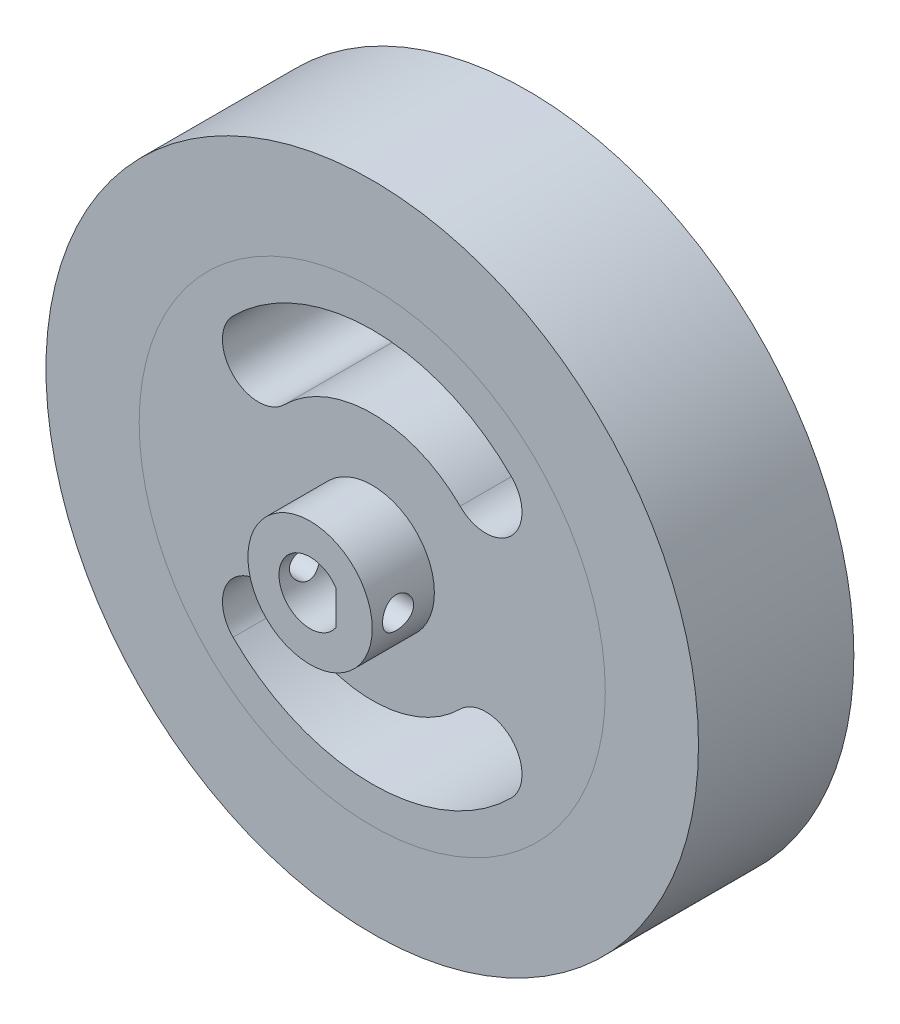
SolidWorks part; units mm, degrees
ref_plane "前视基准面" through (0, 0, 0) normal (0, 0, 1) x (1, 0, 0)
ref_plane "上视基准面" through (0, 0, 0) normal (0, 1, 0) x (1, 0, 0)
ref_plane "右视基准面" through (0, 0, 0) normal (1, 0, 0) x (0, 0, -1)
sketch "草图1" plane through (0, 0, 0) normal (0, 0, 1) x (1, 0, 0)
  circle A0 centre (0, 0) radius 31.5
  dimension "D1" = 63
extrude "凸台-拉伸1" add sketch "草图1" along normal blind 15
sketch "草图2" plane through (0, 0, 15) normal (0, 0, 1) x (1, 0, 0)
  circle A0 centre (0, 0) radius 12.5
  dimension "D1" = 25
sketch "草图3" plane through (0, 0, 0) normal (0, 0, -1) x (-1, 0, 0)
  circle A0 centre (0, 0) radius 3
  dimension "D1" = 6
extrude "切除-拉伸2" cut sketch "草图3" against normal through all
sketch "草图4" plane through (0, 0, 15) normal (0, 0, 1) x (1, 0, 0)
  circle A0 centre (0, 0) radius 14.5
  dimension "D1" = 29
sketch "草图14" plane through (0, 0, 15) normal (0, 0, 1) x (1, 0, 0)
  circle A0 centre (0, 0) radius 3
  circle A1 centre (0, 0) radius 6
  dimension "D1" = 12
  dimension "D2" = 6
extrude "凸台-拉伸3" add sketch "草图14" along normal blind 6
sketch "草图15" plane through (0, 0, 0) normal (0, 0, -1) x (-1, 0, 0)
  circle A0 centre (0, 0) radius 22.5
  dimension "D1" = 45
split line "分割线1"
sketch "草图16" plane through (0, 0, 15) normal (0, 0, 1) x (1, 0, 0)
  circle A0 centre (0, 0) radius 22.5
  dimension "D1" = 45
split line "分割线2"
sketch "草图19" plane through (0, 0, 21) normal (0, 0, 1) x (1, 0, 0)
  line L0 (2.5, 1.6583) -> (2.5, -1.6583)
  arc A0 (2.5, -1.6583) -> (2.5, 1.6583) centre (0, 0) ccw
  circle A1 centre (0, 0) radius 3 construction
  dimension "D1" = 2.5
extrude "凸台-拉伸4" add sketch "草图19" against normal up to surface (21 mm away) up to face at (22.5, 0, 0)
sketch "草图18" plane through (0, 0, 0) normal (1, 0, 0) x (0, 0, -1)
  line L0 (-21, 6) -> (-21, -6) construction
  line L1 (-18.5, 0) -> (0, 0) construction
  circle A0 centre (-18.5, 0) radius 1.5
  dimension "D1" = 3
  dimension "D2" = 2.5
extrude "切除-拉伸3" cut sketch "草图18" against normal through all both and the other way through all
cosmetic thread "装饰螺纹线1" parameters "D2"=4
cosmetic thread "装饰螺纹线2" parameters "D2"=4
sketch "草图20" plane through (0, 0, 15) normal (0, 0, 1) x (1, 0, 0)
  line L0 (-10.9602, 10.9602) -> (0, 0) construction
  line L1 (0, 0) -> (10.9602, 10.9602) construction
  line L2 (0, 0) -> (38.8034, 0) construction
  arc A0 (8.4853, 8.4853) -> (-8.4853, 8.4853) centre (0, 0) ccw
  arc A1 (13.435, 13.435) -> (-13.435, 13.435) centre (0, 0) ccw
  arc A3 (8.4853, 8.4853) -> (13.435, 13.435) centre (10.9602, 10.9602) ccw
  arc A4 (-13.435, 13.435) -> (-8.4853, 8.4853) centre (-10.9602, 10.9602) ccw
  arc A5 (8.4853, -8.4853) -> (13.435, -13.435) centre (10.9602, -10.9602) cw
  arc A6 (8.4853, -8.4853) -> (-8.4853, -8.4853) centre (0, 0) cw
  arc A7 (-13.435, -13.435) -> (-8.4853, -8.4853) centre (-10.9602, -10.9602) cw
  arc A8 (13.435, -13.435) -> (-13.435, -13.435) centre (0, 0) cw
  dimension "D1" = 24
  dimension "D2" = 38
  dimension "D3" = 45
  dimension "D4" = 135
extrude "切除-拉伸5" cut sketch "草图20" against normal through all both and the other way through all
